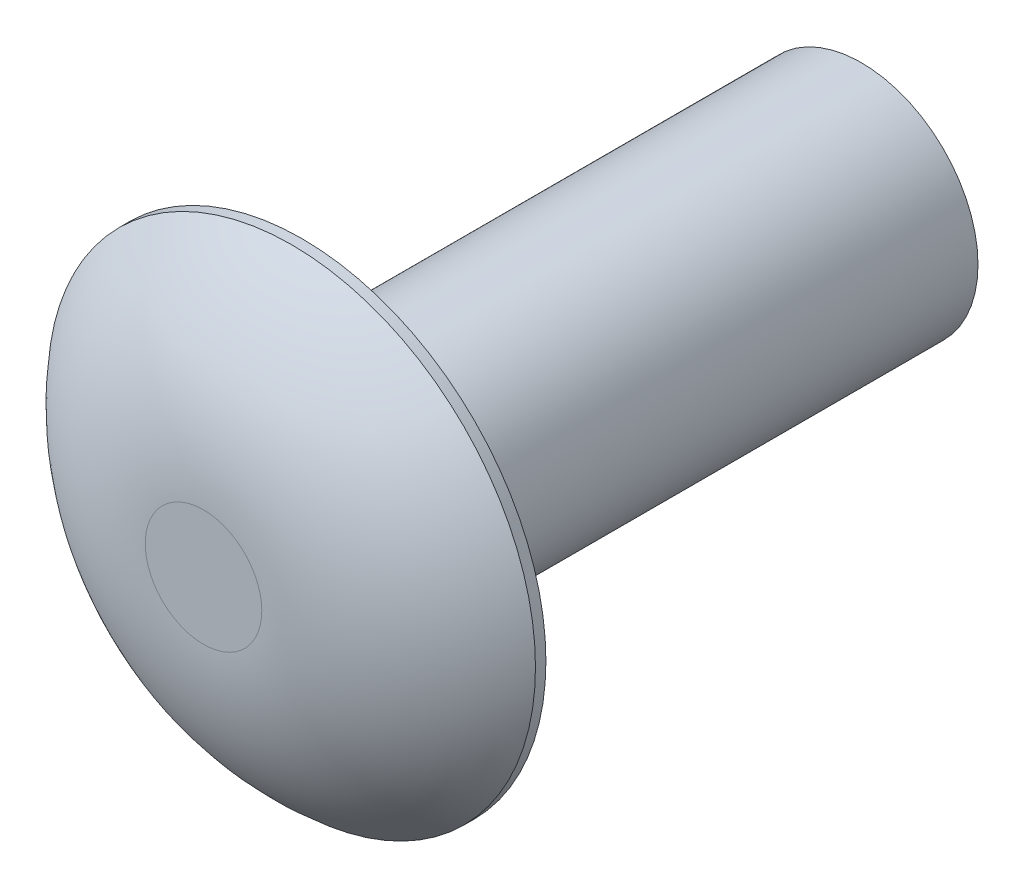
SolidWorks part; units mm, degrees
ref_plane "Front" through (0, 0, 0) normal (0, 0, 1) x (1, 0, 0)
ref_plane "Top" through (0, 0, 0) normal (0, 1, 0) x (1, 0, 0)
ref_plane "Right" through (0, 0, 0) normal (1, 0, 0) x (0, 0, -1)
sketch "layout" plane through (0, 0, 0) normal (1, 0, 0) x (0, 0, -1)
  line L0 (-20.7264, 0) -> (-1.6764, 0) construction
  line L1 (-1.6764, 0) -> (0, 0) construction
  line L2 (0, 0) -> (9.525, 0) construction
  line L3 (9.525, 0) -> (11.2014, 0) construction
  line L8 (0, 4.1529) -> (0, -4.1529) construction
  line L9 (9.525, 1.9844) -> (9.525, -1.9844) construction
  point P7 (-1.6764, 4.1529)
  point P10 (0, 4.1529)
  point P17 (0, -4.1529)
  point P18 (9.525, 1.9844)
  point P19 (-20.7264, 0)
  point P21 (9.525, -1.9844)
  dimension "D5" = 1.6764
sketch "Sketch2" plane through (0, 0, 0) normal (1, 0, 0) x (0, 0, -1)
  line L0 (-20.7264, 0) -> (-20.7264, 0.9922)
  line L1 (-20.7264, 0.9922) -> (0, 0.9922) construction
  line L2 (0, 4.1529) -> (0, -4.1529) construction
  line L3 (0, 0) -> (0, 4.1529) construction
  line L4 (-1.6764, 0) -> (-1.6764, -1.8472) construction
  line L5 (9.525, 1.9844) -> (0, 1.9844)
  line L6 (9.525, 1.9844) -> (9.525, 0) construction
  line L7 (9.9441, 1.9844) -> (9.9441, -1.9844) construction
  line L8 (8.6868, 0) -> (9.525, 0) construction
  line L9 (11.2014, 0) -> (11.2014, 1.9844) construction
  line L10 (9.525, 1.9844) -> (9.9441, 1.9844) construction
  line L11 (9.9441, 1.9844) -> (10.3632, 1.9844) construction
  line L12 (-20.7264, 0) -> (9.525, 0)
  line L13 (-1.6764, 0.9922) -> (-1.6764, 0) construction
  line L14 (10.3632, 1.9844) -> (10.7823, 1.9844) construction
  line L15 (10.7823, 1.9844) -> (11.2014, 1.9844) construction
  line L16 (9.525, 1.8709) -> (9.525, 1.9844)
  line L17 (9.525, 1.8709) -> (9.525, 0)
  line L19 (0, 1.9844) -> (0, 4.1529)
  line L20 (-1.6764, 0.9922) -> (-20.7264, 0.9922)
  line L22 (0, 4.1529) -> (-0.1778, 4.1529)
  arc A2 (-0.1778, 4.1529) -> (-1.6764, 0.9922) centre (2.406, 0.9922) ccw
  ellipse E0 centre (9.9441, 0) end of major axis (9.9441, -1.9844) minor radius 1.2573 (11.2014, 0) -> (9.525, 1.8709) ccw construction
  point P20 (9.525, 0.9922)
  dimension "D1" = 0.1778
revolve "Revolve1" add sketch "Sketch2" angle 360 about L12
sketch "Sketch3" plane through (0, 0, 0) normal (0, 1, 0) x (1, 0, 0)
  line L0 (0, -20.7264) -> (1.1954, -19.1685)
  line L1 (-0.9922, -20.7264) -> (0.9922, -20.7264) construction
  line L3 (0, -20.7264) -> (0, -21.2344) construction
  line L4 (0, -20.7264) -> (-1.1954, -19.1685)
  line L5 (-1.1954, -19.1685) -> (-1.1954, -21.2344)
  line L6 (-1.1954, -21.2344) -> (1.1954, -21.2344)
  line L7 (1.1954, -21.2344) -> (1.1954, -19.1685)
  dimension "D1" = 75
  dimension "D2" = 0.2032
  dimension "D3" = 0.508
extrude "Cut-Extrude1" cut sketch "Sketch3" against normal through all both and the other way through all
sketch "Sketch5" plane through (0, 0, 0) normal (1, 0, 0) x (0, 0, -1)
  line L0 (-20.7264, 0) -> (-19.4334, 1.3097)
  line L1 (-20.7264, -0.9922) -> (-20.7264, 0.9922) construction
  line L2 (-19.4334, 1.3097) -> (-21.0439, 1.3097)
  line L3 (-21.0439, 1.3097) -> (-21.0439, -1.3097)
  line L4 (-21.0439, -1.3097) -> (-19.4334, -1.3097)
  line L5 (-19.4334, -1.3097) -> (-20.7264, 0)
  line L6 (-20.7264, 0) -> (-9.2614, 0) construction
  line L7 (-1.6764, 0.9922) -> (-20.7264, 0.9922) construction
  line L8 (-19.4334, 0) -> (-19.4334, 1.3097) construction
  ellipse E0 centre (-20.7264, 0) end of major axis (-22.0194, 0) minor radius 0.9922 (-20.7264, -0.9922) -> (-20.7264, 0.9922) ccw construction
  dimension "D1" = 0.3175
  dimension "D2" = 0.3175
extrude "Cut-Extrude2" cut sketch "Sketch5" against normal through all both and the other way through all
fillet "Fillet2" radius 0.254 1 edges at (1.9844, 0, 0)
sketch "Sketch6" plane through (0, 0, 0) normal (1, 0, 0) x (0, 0, -1)
  line L0 (-6.5913, 0.9922) -> (-6.4389, 0.9922)
  line L1 (-20.7264, 0) -> (-1.6764, 0) construction
  line L2 (-6.4389, 0.9922) -> (-6.4389, -0.9922) construction
  line L3 (-1.6764, 0.9922) -> (-1.6764, -0.9922) construction
  line L4 (-19.7468, -0.9922) -> (-1.6764, -0.9922) construction
  arc A0 (-6.5913, 0.9922) -> (-6.4389, 0.9922) centre (-6.5151, 0.9922) ccw
  point P11 (-6.4389, 0)
  dimension "D2" = 0.0762
  dimension "D1" = 14.2875
  dimension "D3" = 19.05
revolve "Cut-Revolve1" cut sketch "Sketch6" angle 360 about L1
pattern_linear "LPattern1" count 18 spacing 0.762 along (0, 0, 1) of "Cut-Revolve1"
sketch "Sketch7" plane through (0, 0, 0) normal (0, 1, 0) x (1, 0, 0)
  line L0 (0.9922, -1.6764) -> (-0.9922, -1.6764) construction
  line L1 (-0.9922, -1.6764) -> (1.6457, -1.6764)
  line L2 (-0.9922, -1.6764) -> (-0.9922, -21.9966)
  line L3 (-0.9922, -21.9966) -> (1.6457, -21.9966)
  line L4 (1.6457, -1.6764) -> (1.6457, -21.9966)
  arc A0 (-4.1529, -0.1778) -> (-0.9922, -1.6764) centre (-0.9922, 2.406) ccw construction
extrude "Cut-Extrude3" cut sketch "Sketch7" against normal through all both and the other way through all
equation "\"D5@layout\"=\"Head Height@layout\"*1"
equation "\"D9@layout\"=\"length@layout\"*2"
equation "\"D2@Sketch5\"=\"D1@Sketch5\""
equation "\"D1@Sketch6\"=\"D3@Sketch6\"*.75"
